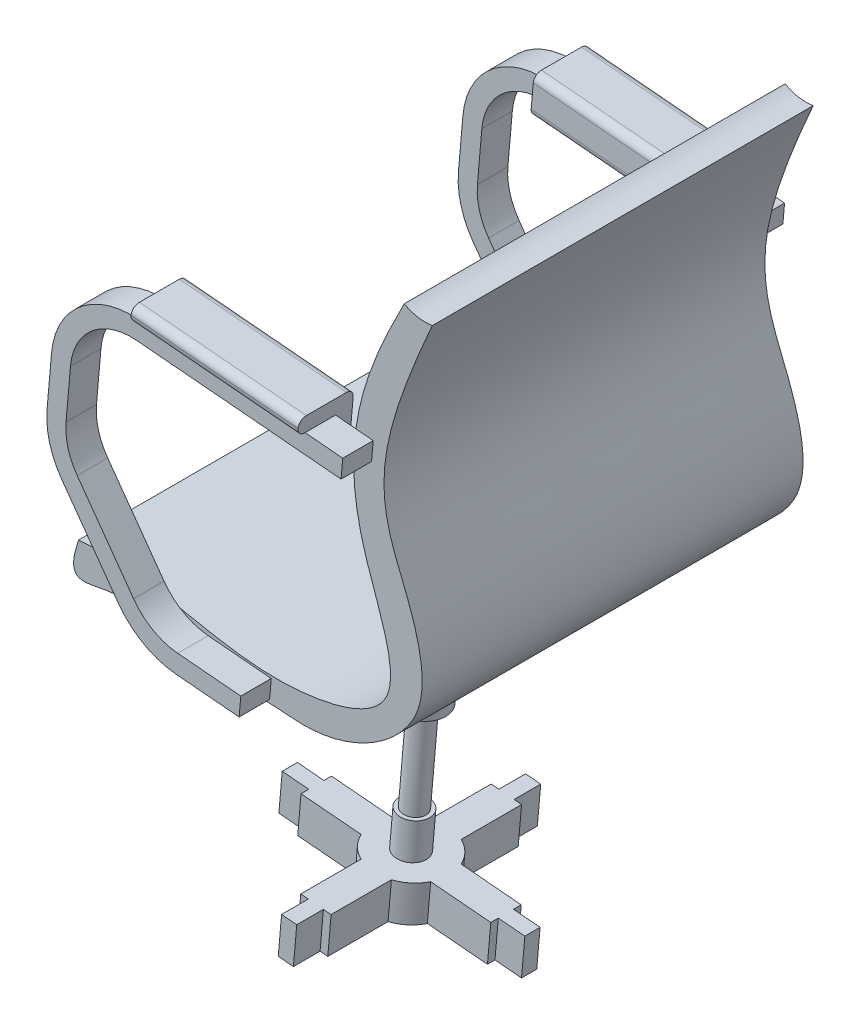
SolidWorks part; units mm, degrees
ref_plane "Front Plane" through (0, 0, 0) normal (0, 0, 1) x (1, 0, 0)
ref_plane "Top Plane" through (0, 0, 0) normal (0, 1, 0) x (1, 0, 0)
ref_plane "Right Plane" through (0, 0, 0) normal (1, 0, 0) x (0, 0, -1)
sketch "Sketch2" plane through (0, 0, 0) normal (0, 0, 1) x (1, 0, 0)
  spline S0 degree 3 poles (-70.3325, -37.7854) (-77.5194, -54.02) (-77.8554, -60.2025) (-72.362, -73.1435) (-70.3638, -80.0728) (-76.0291, -88.7872) (-83.3067, -92.1595) (-95.0894, -90.9242) (-101.813, -91.7185) (-113.5654, -87.8979) (-119.0662, -92.2496) (-116.7822, -85.4021) knots 0 0 0 0 0.246327 0.276347 0.434809 0.461411 0.619876 0.661404 0.852766 0.884375 1 1 1 1
  spline S1 degree 2 poles (-74.0115, -37.1406) (-72.3473, -38.0935) (-70.3325, -37.7854) knots 0 0 0 1 1 1
  spline S3 degree 3 poles (-74.0115, -37.1406) (-79.5937, -47.9439) (-84.0791, -60.793) (-71.7452, -84.69) (-95.5615, -90.8338) (-106.8514, -84.2235) (-116.7822, -85.4021) knots 0 0 0 0 0.357319 0.535771 0.679015 1 1 1 1
extrude "Boss-Extrude1" add sketch "Sketch2" against normal blind 50
sketch "Sketch3" plane through (0, 0, -50) normal (0, 0, -1) x (-1, 0, 0)
  line L0 (78.3074, -57.2262) -> (105.162, -54.8767)
  line L1 (113.8289, -62.149) -> (114.4087, -68.7771)
  line L2 (112.939, -74.1383) -> (105.5462, -84.4412)
  line L3 (99.7436, -87.7468) -> (91.4701, -88.4707)
  line L4 (78.0896, -54.7357) -> (104.9442, -52.3862)
  line L5 (116.3193, -61.9311) -> (116.8992, -68.5592)
  line L6 (114.9702, -75.5957) -> (107.5774, -85.8987)
  line L7 (99.9615, -90.2373) -> (91.688, -90.9612)
  line L8 (78.0896, -54.7357) -> (78.3074, -57.2262)
  line L9 (91.4701, -88.4707) -> (91.688, -90.9612)
  arc A0 (114.4087, -68.7771) -> (112.939, -74.1383) centre (106.4392, -69.4743) cw
  arc A1 (113.8289, -62.149) -> (105.162, -54.8767) centre (105.8593, -62.8463) ccw
  arc A2 (99.7436, -87.7468) -> (105.5462, -84.4412) centre (99.0463, -79.7773) ccw
  arc A3 (116.3193, -61.9311) -> (104.9442, -52.3862) centre (105.8593, -62.8463) ccw
  arc A4 (116.8992, -68.5592) -> (114.9702, -75.5957) centre (106.4392, -69.4743) cw
  arc A5 (99.9615, -90.2373) -> (107.5774, -85.8987) centre (99.0463, -79.7773) ccw
  dimension "D1" = 8
  dimension "D2" = 8
  dimension "D3" = 2.5
extrude "Boss-Extrude2" add sketch "Sketch3" along normal blind 4
ref_plane "Plane2" through (-99.6013, 8.7141, 0) normal (0.9962, -0.0872, 0) x (0, 0, -1)
sketch "Sketch5" plane through (-99.6013, 8.7141, 0) normal (0.9962, -0.0872, 0) x (0, 0, -1)
  line L0 (53.9981, -61.35) -> (49.9495, -61.35)
  line L1 (49.9495, -61.35) -> (49.9495, -63.8306)
  line L2 (53.9981, -61.35) -> (54.0099, -61.35)
  line L3 (55.0099, -60.35) -> (55.0099, -60.2872)
  line L4 (54.0099, -59.2872) -> (48.7759, -59.2872)
  line L5 (47.7759, -60.2872) -> (47.7759, -63.4131)
  line L6 (48.7759, -64.4131) -> (49.9495, -64.4131)
  line L7 (49.9495, -64.4131) -> (49.9495, -63.8306)
  arc A0 (54.0099, -61.35) -> (55.0099, -60.35) centre (54.0099, -60.35) ccw
  arc A1 (55.0099, -60.2872) -> (54.0099, -59.2872) centre (54.0099, -60.2872) ccw
  arc A2 (48.7759, -64.4131) -> (47.7759, -63.4131) centre (48.7759, -63.4131) cw
  arc A3 (47.7759, -60.2872) -> (48.7759, -59.2872) centre (48.7759, -60.2872) cw
  dimension "D1" = 1
extrude "Boss-Extrude3" add sketch "Sketch5" along normal blind 22
ref_plane "Plane3" through (0, 0, -25) normal (0, 0, -1) x (-1, 0, 0)
mirror "Mirror1" about plane through (0, 0, -25) normal (0, 0, -1) of "Boss-Extrude2", "Boss-Extrude3"
ref_plane "Plane4" through (-12.1399, -138.7572, 0) normal (0.0872, 0.9962, 0) x (0.9962, -0.0872, 0)
sketch "Sketch8" plane through (-12.1399, -138.7572, 0) normal (0.0872, 0.9962, 0) x (0.9962, -0.0872, 0)
  line L0 (-84.4691, 29.3075) -> (-76.5516, 29.3075)
  line L1 (-87.0516, 22.725) -> (-87.0516, 14.8075)
  line L2 (-101.5516, 25.3075) -> (-93.6342, 25.3075)
  line L3 (-101.5516, 25.3075) -> (-101.5516, 26.3201)
  line L4 (-101.5516, 29.3075) -> (-93.6342, 29.3075)
  line L5 (-76.5516, 25.3075) -> (-76.5516, 26.295)
  line L6 (-84.4691, 25.3075) -> (-76.5516, 25.3075)
  line L7 (-91.0516, 22.725) -> (-91.0516, 14.8075)
  line L8 (-91.0516, 39.8075) -> (-90.0391, 39.8075)
  line L9 (-91.0516, 39.8075) -> (-91.0516, 31.8901)
  line L10 (-91.0516, 14.8075) -> (-90.0642, 14.8075)
  line L11 (-87.0516, 39.8075) -> (-87.0516, 31.8901)
  line L12 (-105.0516, 26.3201) -> (-101.5516, 26.3201)
  line L13 (-90.0642, 11.3075) -> (-88.0642, 11.3075)
  line L14 (-90.0642, 11.3075) -> (-90.0642, 14.8075)
  line L15 (-101.5516, 28.3201) -> (-101.5516, 29.3075)
  line L16 (-88.0642, 11.3075) -> (-88.0642, 14.8075)
  line L17 (-90.0642, 11.3075) -> (-88.0642, 14.8075) construction
  line L18 (-90.0642, 14.8075) -> (-88.0642, 11.3075) construction
  line L19 (-105.0516, 28.3201) -> (-105.0516, 26.3201)
  line L20 (-105.0516, 28.3201) -> (-101.5516, 28.3201)
  line L21 (-90.0391, 43.3075) -> (-90.0391, 39.8075)
  line L22 (-88.0391, 43.3075) -> (-90.0391, 43.3075)
  line L23 (-88.0391, 43.3075) -> (-88.0391, 39.8075)
  line L24 (-73.0516, 28.295) -> (-76.5516, 28.295)
  line L25 (-73.0516, 26.295) -> (-73.0516, 28.295)
  line L26 (-73.0516, 26.295) -> (-76.5516, 26.295)
  line L27 (-88.0391, 39.8075) -> (-87.0516, 39.8075)
  line L28 (-76.5516, 28.295) -> (-76.5516, 29.3075)
  line L29 (-88.0642, 14.8075) -> (-87.0516, 14.8075)
  arc A0 (-91.0516, 31.8901) -> (-93.6342, 29.3075) centre (-89.0516, 27.3075) ccw
  arc A1 (-84.4691, 29.3075) -> (-87.0516, 31.8901) centre (-89.0516, 27.3075) ccw
  arc A2 (-87.0516, 22.725) -> (-84.4691, 25.3075) centre (-89.0516, 27.3075) ccw
  arc A3 (-93.6342, 25.3075) -> (-91.0516, 22.725) centre (-89.0516, 27.3075) ccw
  point P18 (-89.0642, 13.0575)
  point P38 (-89.0516, 27.3075)
  dimension "D1" = 10
  dimension "D2" = 25
  dimension "D3" = 4
  dimension "D4" = 25
  dimension "D5" = 4
  dimension "D6" = 3.5
  dimension "D7" = 2
  dimension "D8" = 4
extrude "Boss-Extrude4" add sketch "Sketch8" along normal blind 5 separate body
sketch "Sketch11" plane through (-11.7041, -133.7762, 0) normal (0.0872, 0.9962, 0) x (0.9962, -0.0872, 0)
  circle A0 centre (-89.0516, 27.3075) radius 2
  circle A1 centre (-89.0516, 27.3075) radius 1.5
  dimension "D1" = 4
  dimension "D2" = 3
extrude "Boss-Extrude5" add sketch "Sketch11" along normal blind 5
sketch "Sketch12" plane through (-11.2683, -128.7952, 0) normal (0.0872, 0.9962, 0) x (0.9962, -0.0872, 0)
  circle A0 centre (-89.0516, 27.3075) radius 1.5 construction
  circle A1 centre (-89.0516, 27.3075) radius 1.5
extrude "Boss-Extrude6" add sketch "Sketch12" along normal up to next
sketch "Sketch13" plane through (-8.5942, -98.231, 0) normal (-0.0872, -0.9962, 0) x (0.9962, -0.0872, 0)
  line L0 (-89.0516, -27.3075) -> (-86.9303, -29.4289) construction
  circle A0 centre (-89.0516, -27.3075) radius 3
  dimension "D1" = 3
extrude "Boss-Extrude7" add sketch "Sketch13" along normal blind 18
scale "Scale3" bodies to scale 108 106 scale about origin uniform scaling yes scale factor 8
